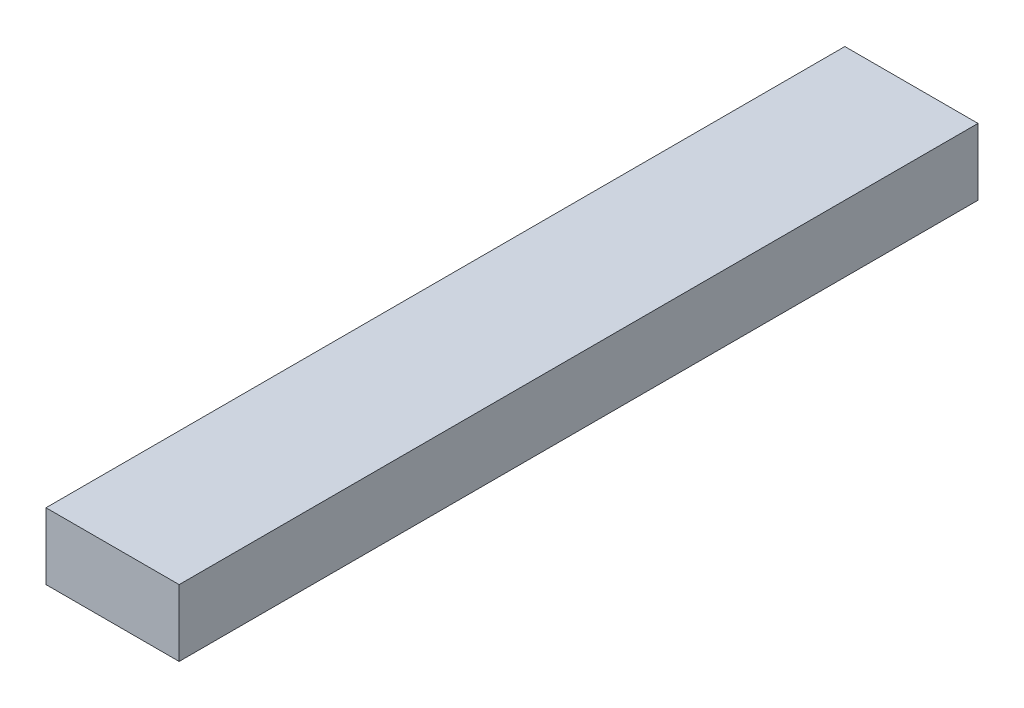
SolidWorks part; units mm, degrees
ref_plane "Front Plane" through (0, 0, 0) normal (0, 0, 1) x (1, 0, 0)
ref_plane "Top Plane" through (0, 0, 0) normal (0, 1, 0) x (1, 0, 0)
ref_plane "Right Plane" through (0, 0, 0) normal (1, 0, 0) x (0, 0, -1)
sketch "Sketch1" plane through (0, 0, 0) normal (0, 0, 1) x (1, 0, 0)
  line L1 (-74.5506, 22.1013) -> (27.0494, 22.1013)
  line L2 (-74.5506, 22.1013) -> (-74.5506, -28.6987)
  line L3 (-74.5506, -28.6987) -> (27.0494, -28.6987)
  line L4 (27.0494, 22.1013) -> (27.0494, -28.6987)
  dimension "D1" = 50.8
  dimension "D2" = 101.6
extrude "Boss-Extrude1" add sketch "Sketch1" along normal blind 609.6
